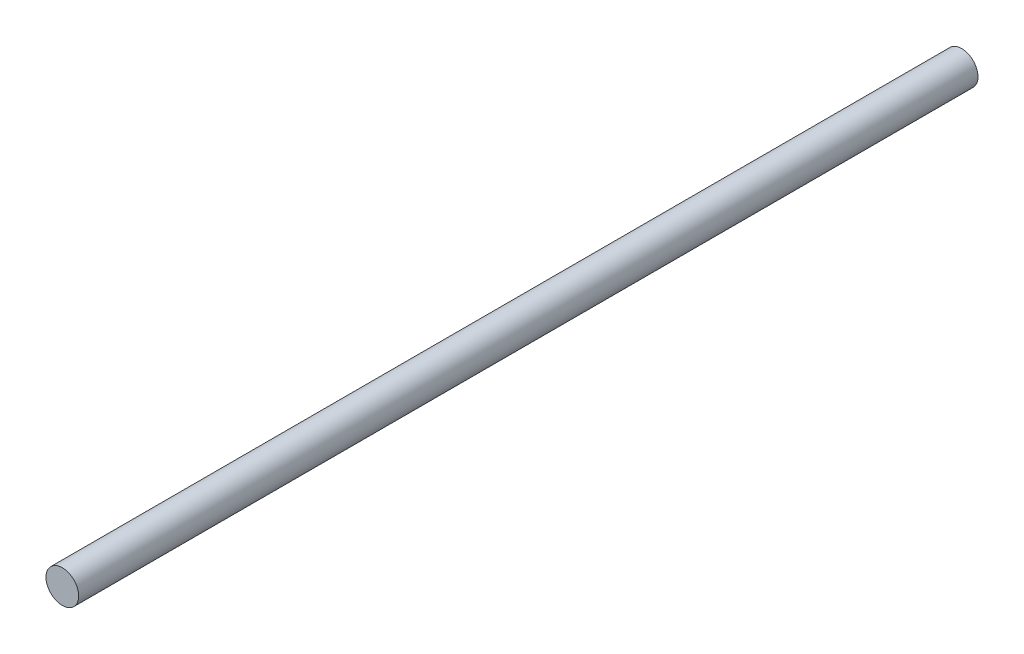
SolidWorks part; units mm, degrees
ref_plane "Ebene vorne" through (0, 0, 0) normal (0, 0, 1) x (1, 0, 0)
ref_plane "Ebene oben" through (0, 0, 0) normal (0, 1, 0) x (1, 0, 0)
ref_plane "Ebene rechts" through (0, 0, 0) normal (1, 0, 0) x (0, 0, -1)
sketch "Sketch1" plane through (0, 0, 0) normal (0, 0, 1) x (1, 0, 0)
  circle A0 centre (0, 0) radius 4
  dimension "D1" = 8
extrude "Boss-Extrude1" add sketch "Sketch1" along normal blind 220
